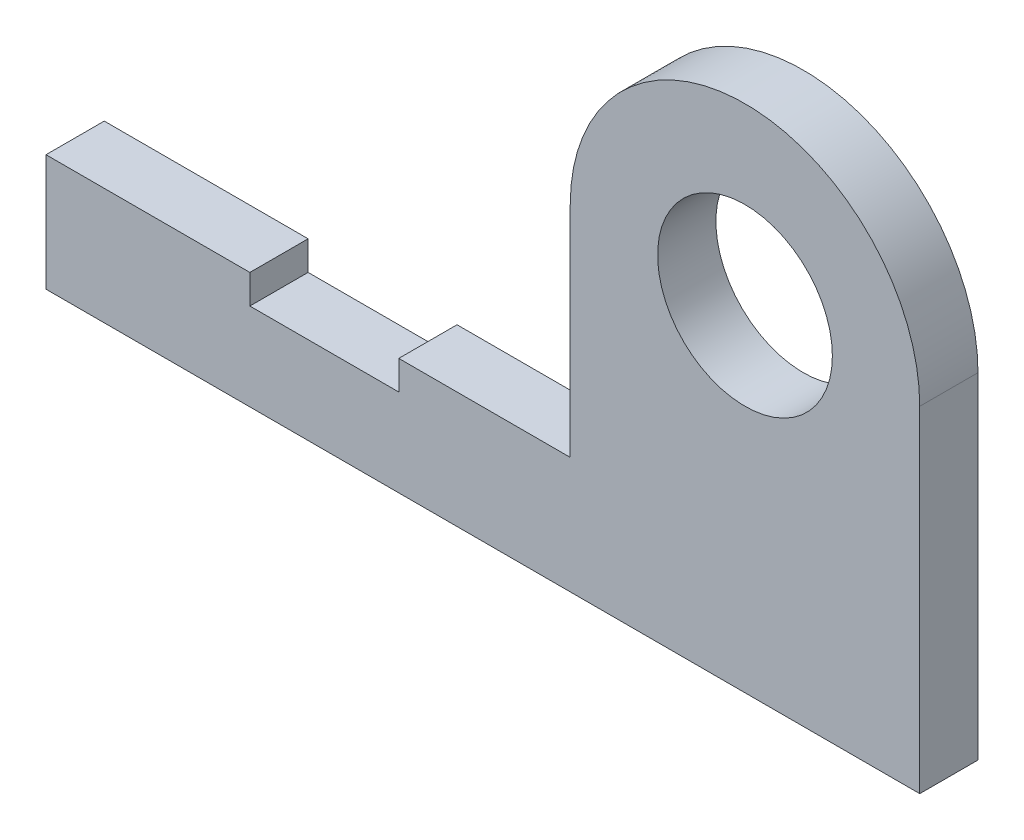
SolidWorks part; units mm, degrees
ref_plane "Front Plane" through (0, 0, 0) normal (0, 0, 1) x (1, 0, 0)
ref_plane "Top Plane" through (0, 0, 0) normal (0, 1, 0) x (1, 0, 0)
ref_plane "Right Plane" through (0, 0, 0) normal (1, 0, 0) x (0, 0, -1)
sketch "Sketch1" plane through (0, 0, 0) normal (0, 0, 1) x (1, 0, 0)
  line L0 (0, 0) -> (0, 20)
  line L1 (0, 20) -> (35, 20)
  line L2 (35, 20) -> (35, 15)
  line L3 (35, 15) -> (60.5639, 15)
  line L4 (60.5639, 15) -> (60.5639, 20)
  line L5 (60.5639, 20) -> (90, 20)
  line L6 (90, 20) -> (90, 57.594)
  line L7 (150, 57.594) -> (150, 0)
  line L8 (150, 0) -> (0, 0)
  arc A0 (90, 57.594) -> (150, 57.594) centre (120, 57.594) cw
  circle A1 centre (120, 57.594) radius 15
  point P12 (120, 87.594)
  dimension "D1" = 20
  dimension "D6" = 30
  dimension "D2" = 35
  dimension "D3" = 15
  dimension "D4" = 5
  dimension "D5" = 30
  dimension "D7" = 150
extrude "Boss-Extrude3" add sketch "Sketch1" along normal mid plane 10
